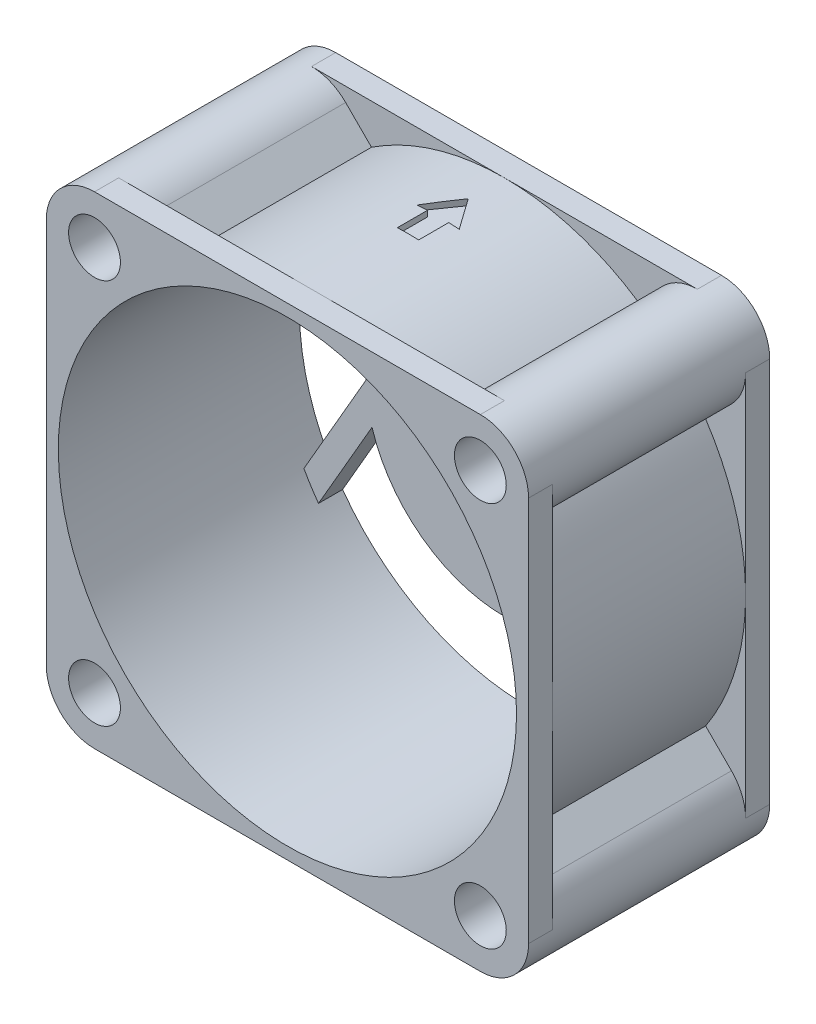
SolidWorks part; units mm, degrees
material "PW100:Mi:0:3:C1:0:1:2:Re:26:"
ref_plane "Front" through (0, 0, 0) normal (0, 0, 1) x (1, 0, 0)
ref_plane "Top" through (0, 0, 0) normal (0, 1, 0) x (1, 0, 0)
ref_plane "Right" through (0, 0, 0) normal (1, 0, 0) x (0, 0, -1)
sketch "Support-Front" plane through (0, 0, 0) normal (0, 0, 1) x (1, 0, 0)
  line L0 (-20, 0) -> (20, 0) construction
  line L1 (0, 20) -> (0, -20) construction
  line L2 (20, -16) -> (20, 16)
  line L3 (-20, -16) -> (-20, 16)
  line L4 (16, 20) -> (-16, 20)
  line L5 (16, -20) -> (-16, -20)
  line L6 (0, 20) -> (0, 26.6274) construction
  arc A0 (20, 16) -> (16, 20) centre (16, 16) ccw
  arc A1 (-20, 16) -> (-16, 20) centre (-16, 16) cw
  arc A2 (-20, -16) -> (-16, -20) centre (-16, -16) ccw
  arc A3 (20, -16) -> (16, -20) centre (16, -16) cw
  circle A4 centre (16, 16) radius 2.15
  circle A5 centre (-16, 16) radius 2.15
  circle A6 centre (-16, -16) radius 2.15
  circle A7 centre (16, -16) radius 2.15
  circle A8 centre (0, 0) radius 19
  circle A9 centre (0, 0) radius 11.5
  circle A10 centre (0, 0) radius 20
  circle A11 centre (0, 0) radius 26.6274 construction
  dimension "Diam-Fixing-Hole" = 4.3
  dimension "Diam-Fan-Hole" = 38
  dimension "Diam-Fixing-Plate-Fan" = 23
  dimension "Dist-Fixing-Hole" = 32
  dimension "Width" = 40
sketch "Support-Right" plane through (0, 0, 0) normal (1, 0, 0) x (0, 0, -1)
  line L0 (-20, 0) -> (0, 0) construction
  line L1 (-10, 20) -> (-10, -20) construction
  line L2 (-2, 20) -> (-2, -20)
  line L3 (-20, 20) -> (0, 20)
  line L4 (-20, 20) -> (-20, -20)
  line L5 (-20, -20) -> (0, -20)
  line L6 (0, 20) -> (0, -20)
  line L7 (-18, 20) -> (-18, -20)
  dimension "Thickness" = 20
  dimension "Thickness-Flange" = 2
sketch "Support-Front-Reinforcment-Place" plane through (0, 0, 0) normal (0, 0, 1) x (1, 0, 0)
  line L0 (0, 20) -> (0, 0) construction
  line L1 (0, 19) -> (0, 20) construction
  line L2 (6.306, 20) -> (6.6973, 17.7805)
  line L3 (16, 20) -> (-16, 20) construction
  line L4 (-6.306, 20) -> (-6.6973, 17.7805)
  line L5 (6.306, 20) -> (0, 0) construction
  line L6 (-6.306, 20) -> (0, 0) construction
  line L7 (6.306, 20) -> (-6.306, 20)
  circle A3 centre (0, 0) radius 19 construction
  arc A4 (6.6973, 17.7805) -> (-6.6973, 17.7805) centre (0, 0) ccw
  point P10 (0, 19.5)
  dimension "D1" = 20
  dimension "D2" = 35
sketch "Support-Front-Reinforcment-Strip" plane through (0, 0, 0) normal (0, 0, 1) x (1, 0, 0)
  line L0 (11.028, 16.6848) -> (13.1716, 18.8284)
  line L1 (16.6848, 11.028) -> (18.8284, 13.1716)
  line L2 (16, 16) -> (0, 0) construction
  arc A0 (13.1716, 18.8284) -> (18.8284, 13.1716) centre (16, 16) cw
  arc A1 (20, 16) -> (16, 20) centre (16, 16) ccw construction
  circle A3 centre (0, 0) radius 20 construction
  arc A6 (16.6848, 11.028) -> (11.028, 16.6848) centre (0, 0) ccw
sketch "Support-Front-Bone" plane through (0, 0, 0) normal (0, 0, 1) x (1, 0, 0)
  line L0 (-11.3253, -1.997) -> (-16.0464, -10.1741) construction
  line L1 (-11.4963, -0.2931) -> (-16.6312, -9.1871)
  line L2 (-10.9841, -3.4059) -> (-15.4237, -11.0955)
  line L3 (0, 0) -> (0, 20) construction
  line L4 (16, 20) -> (-16, 20) construction
  line L6 (0, 0) -> (-11.3253, -1.997) construction
  circle A0 centre (0, 0) radius 19 construction
  circle A1 centre (0, 0) radius 11.5 construction
  arc A2 (-11.4963, -0.2931) -> (-10.9841, -3.4059) centre (0, 0) ccw
  arc A3 (-16.6312, -9.1871) -> (-15.4237, -11.0955) centre (0, 0) ccw
  dimension "Angle-Bone" = 210
  dimension "Angle-Place-Bone" = 260
  dimension "Thickness-Flange" = 2
sketch "Support-Air-Exhaust" plane through (0, 0, 0) normal (0, 1, 0) x (1, 0, 0)
  line L0 (0, -10) -> (0, -7.5) construction
  line L1 (0, -5) -> (-1.7505, -7.5)
  line L2 (-1.7505, -7.5) -> (-0.8816, -7.5)
  line L3 (-0.8816, -7.5) -> (-0.8816, -10)
  line L4 (-0.8816, -10) -> (0.8816, -10)
  line L5 (0, -5) -> (0, 0) construction
  line L6 (0, -5) -> (-0.8816, -10) construction
  line L10 (-0.8816, -7.5) -> (0, -7.5) construction
  line L11 (0, -7.5) -> (0, -5) construction
  line L12 (0, -5) -> (0, -10) construction
  line L13 (0.8816, -7.5) -> (0.8816, -10)
  line L14 (1.7505, -7.5) -> (0.8816, -7.5)
  line L15 (0, -5) -> (1.7505, -7.5)
  dimension "D1" = 10
  dimension "D2" = 35
  dimension "D3" = 5
ref_plane "Plane1" through (0, 0, 20) normal (0, 0, 1) x (1, 0, 0)
ref_plane "Plane2" through (0, 19.5, 0) normal (0, 1, 0) x (-1, 0, 0)
sketch "Sketch-Body" plane through (0, 0, 0) normal (0, 0, 1) x (1, 0, 0)
  line L4 (-16, -20) -> (16, -20)
  line L5 (-20, 16) -> (-20, -16)
  line L6 (16, 20) -> (-16, 20)
  line L7 (20, -16) -> (20, 16)
  line L8 (-16, -20) -> (16, -20)
  line L9 (-20, 16) -> (-20, -16)
  line L10 (16, 20) -> (-16, 20)
  line L11 (20, -16) -> (20, 16)
  circle A0 centre (0, 0) radius 19 construction
  circle A1 centre (0, 0) radius 19
  arc A4 (-20, -16) -> (-16, -20) centre (-16, -16) ccw
  arc A5 (-16, 20) -> (-20, 16) centre (-16, 16) ccw
  arc A6 (20, 16) -> (16, 20) centre (16, 16) ccw
  arc A7 (16, -20) -> (20, -16) centre (16, -16) ccw
  arc A8 (-20, -16) -> (-16, -20) centre (-16, -16) ccw
  arc A9 (-16, 20) -> (-20, 16) centre (-16, 16) ccw
  arc A10 (20, 16) -> (16, 20) centre (16, 16) ccw
  arc A11 (16, -20) -> (20, -16) centre (16, -16) ccw
  dimension "D1" = 0
extrude "Body" add sketch "Sketch-Body" along normal up to surface (20 mm away) up to plane "Plane1"
sketch "Sketch-Cut-Body" plane through (0, 0, 0) normal (1, 0, 0) x (0, 0, -1)
  line L0 (-20, 0) -> (0, 0) construction
  line L1 (-20, 0) -> (0, 0) construction
  line L4 (-20, 20) -> (0, 20) construction
  line L5 (-18, 20) -> (-18, 26.6274)
  line L6 (-18, 26.6274) -> (-2, 26.6274)
  line L7 (-18, 20) -> (-2, 20)
  line L9 (-2, 26.6274) -> (-2, 20)
  line L10 (-2, 20) -> (-2, -20) construction
  line L11 (-18, 20) -> (-18, -20) construction
revolve "Cut-Body" cut sketch "Sketch-Cut-Body" angle 360 about L1
sketch "Sketch-Reinforcment-Strip" plane through (0, 0, 0) normal (0, 0, 1) x (1, 0, 0)
  line L0 (16.6848, 11.028) -> (18.8284, 13.1716) construction
  line L1 (11.028, 16.6848) -> (13.1716, 18.8284) construction
  line L2 (16.6848, 11.028) -> (18.8284, 13.1716)
  line L3 (11.028, 16.6848) -> (13.1716, 18.8284)
  arc A0 (18.8284, 13.1716) -> (13.1716, 18.8284) centre (16, 16) ccw construction
  circle A1 centre (0, 0) radius 20 construction
  arc A2 (18.8284, 13.1716) -> (13.1716, 18.8284) centre (16, 16) ccw
  arc A3 (16.6848, 11.028) -> (11.028, 16.6848) centre (0, 0) ccw
extrude "Reinforcment-Strip" add sketch "Sketch-Reinforcment-Strip" along normal up to surface (20 mm away) up to plane "Plane1"
pattern_circular "CirPattern-Reinforcment-Strip" count 4 over 360 about axis through (0, 0, 0) along (0, 0, 1) of "Reinforcment-Strip"
sketch "Sketch-Fixing-Hole" plane through (0, 0, 0) normal (0, 0, 1) x (1, 0, 0)
  circle A0 centre (16, 16) radius 2.15 construction
  circle A1 centre (16, 16) radius 2.15
extrude "Fixing-Hole" cut sketch "Sketch-Fixing-Hole" along normal through all
pattern_circular "CirPattern-Fixing-Hole" count 4 over 360 about axis through (0, 0, 0) along (0, 0, 1) of "Fixing-Hole"
sketch "Sketch-Bone" plane through (0, 0, 0) normal (0, 0, 1) x (1, 0, 0)
  line L0 (-10.9841, -3.4059) -> (-15.4237, -11.0955) construction
  line L1 (-11.4963, -0.2931) -> (-16.6312, -9.1871) construction
  line L2 (-10.9841, -3.4059) -> (-15.4237, -11.0955)
  line L3 (-11.4963, -0.2931) -> (-16.6312, -9.1871)
  circle A0 centre (0, 0) radius 19 construction
  circle A1 centre (0, 0) radius 11.5 construction
  arc A2 (-16.6312, -9.1871) -> (-15.4237, -11.0955) centre (0, 0) ccw
  arc A3 (-11.4963, -0.2931) -> (-10.9841, -3.4059) centre (0, 0) ccw
extrude "Bone" add sketch "Sketch-Bone" along normal blind 2
pattern_circular "CirPattern-Bone" count 3 over 360 about axis through (0, 0, 0) along (0, 0, 1) of "Bone"
sketch "Sketch-Fixing-Plate-Fan" plane through (0, 0, 0) normal (0, 0, 1) x (1, 0, 0)
  circle A0 centre (0, 0) radius 11.5 construction
  circle A1 centre (0, 0) radius 11.5
extrude "Fixing-Plate-Fan" add sketch "Sketch-Fixing-Plate-Fan" along normal blind 2
sketch "Sketch2" plane through (0, 19.5, 0) normal (0, 1, 0) x (-1, 0, 0)
  line L7 (0.8816, 7.5) -> (0.8816, 10)
  line L8 (1.7505, 7.5) -> (0.8816, 7.5)
  line L9 (0, 5) -> (1.7505, 7.5)
  line L10 (-1.7505, 7.5) -> (0, 5)
  line L11 (-1.7505, 7.5) -> (0, 5)
  line L12 (-0.8816, 7.5) -> (-1.7505, 7.5)
  line L13 (0.8816, 10) -> (-0.8816, 10)
  line L14 (0.8816, 7.5) -> (0.8816, 10)
  line L15 (1.7505, 7.5) -> (0.8816, 7.5)
  line L16 (0, 5) -> (1.7505, 7.5)
  line L17 (-0.8816, 7.5) -> (-1.7505, 7.5)
  line L18 (-0.8816, 10) -> (-0.8816, 7.5)
  line L19 (-0.8816, 10) -> (-0.8816, 7.5)
  line L20 (0.8816, 10) -> (-0.8816, 10)
  dimension "D1" = 0
extrude "Air-Exhaust" cut sketch "Sketch2" along normal through all
equation "\"Diam-Fan-Hole@Support-Front\" = \"Width@Support-Front\"-2"
